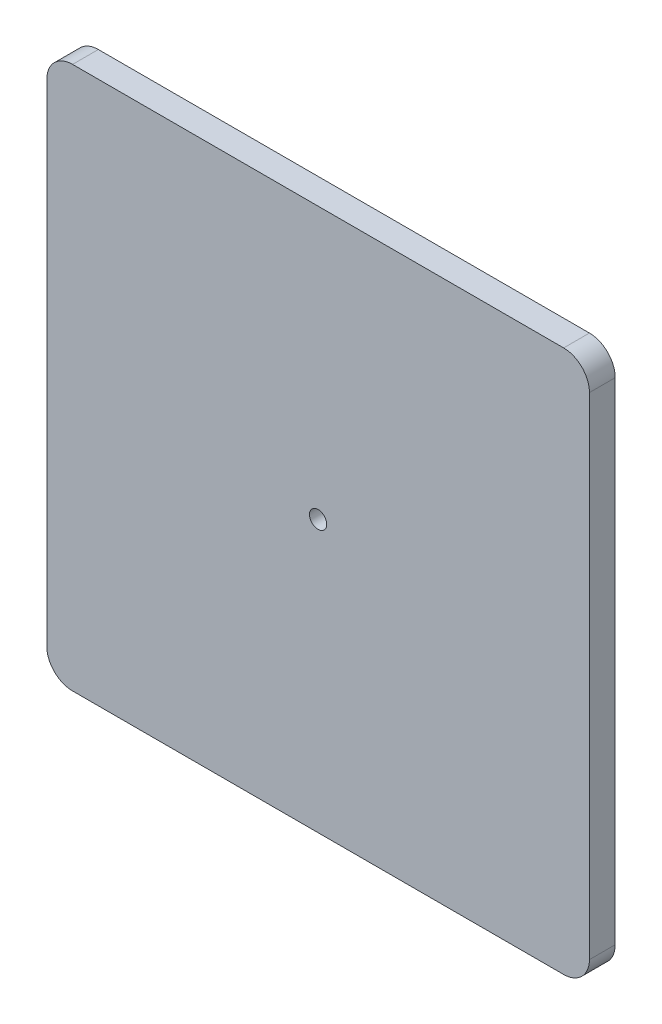
SolidWorks part; units mm, degrees
ref_plane "Front Plane" through (0, 0, 0) normal (0, 0, 1) x (1, 0, 0)
ref_plane "Top Plane" through (0, 0, 0) normal (0, 1, 0) x (1, 0, 0)
ref_plane "Right Plane" through (0, 0, 0) normal (1, 0, 0) x (0, 0, -1)
sketch "Baseplate" plane through (0, 0, 0) normal (0, 0, 1) x (1, 0, 0)
  line L2 (-100, 100) -> (100, 100)
  line L3 (-100, 100) -> (-100, -100)
  line L4 (-100, -100) -> (100, -100)
  line L5 (100, 100) -> (100, -100)
  line L6 (-100, 100) -> (100, -100) construction
  line L7 (-100, -100) -> (100, 100) construction
  point P2 (0, 0)
  dimension "D1" = 200
  dimension "D2" = 200
extrude "Boss-Extrude1" add sketch "Baseplate" along normal blind 9.5
sketch "LIDAR PLACEMENT" [suppressed] plane through (0, 0, 3) normal (0, 0, 1) x (1, 0, 0)
  circle A0 centre (0, 0) radius 51.65
  circle A1 centre (44.45, 0) radius 1.015
  dimension "D1" = 103.3
  dimension "2.03" = 2.03
  dimension "D2" = 44.45
fillet "Fillet1" radius 9.5 4 edges at (-100, -100, 4.75) (100, -100, 4.75) (100, 100, 4.75) (-100, 100, 4.75)
hole_wizard "1/4 Inch Bolt Hole" positions "Sketch7" profile "Sketch8" hole size "1/4" standard "ANSI Inch" end condition through all
sketch "Sketch7" plane through (0, 0, 0) normal (0, 0, -1) x (-1, 0, 0)
  point P0 (0, 0)
sketch "Sketch8" plane through (0, 0, 0) normal (1, 0, 0) x (0, 1, 0)
  line L0 (0, 0) -> (0, 9.5)
  line L1 (0, 9.5) -> (3.175, 9.5)
  line L2 (3.175, 9.5) -> (3.175, 0.635)
  line L3 (3.175, 0.635) -> (3.81, 0)
  line L5 (3.81, 0) -> (0, 0)
  line L6 (-3.175, 0.635) -> (-3.81, 0) construction
  line L11 (0, -6.35) -> (0, 107.95) construction
  dimension "Thru Hole Dia." = 6.35
  dimension "Thru Hole Depth" = 9.5
  dimension "Near C'Sink Dia." = 7.62
  dimension "Near C'Sink Angle" = 90
hole_wizard "5/32 Dowel Hole" positions "Sketch13" profile "Sketch14" hole size "5/32" standard "ANSI Inch"
sketch "Sketch13" plane through (0, 0, 0) normal (0, 0, -1) x (-1, 0, 0)
  point P0 (-44.5, 0)
  point P2 (44.45, 0)
  dimension "D1" = 44.45
  dimension "D2" = 44.5
sketch "Sketch14" plane through (44.5, 0, 0) normal (1, 0, 0) x (0, 1, 0)
  line L0 (0, 0) -> (0, 7.1923)
  line L1 (0, 7.1923) -> (1.9844, 6)
  line L2 (1.9844, 6) -> (1.9844, 0.5328)
  line L3 (1.9844, 0.5328) -> (2.6194, 0)
  line L5 (2.6194, 0) -> (0, 0)
  line L6 (-1.9844, 0.5328) -> (-2.6194, 0) construction
  line L10 (0, 7.1923) -> (-1.9844, 6) construction
  line L11 (0, -6.35) -> (0, 107.95) construction
  dimension "Hole Dia." = 3.9688
  dimension "Hole Depth" = 6
  dimension "Near C'Sink Dia." = 5.2387
  dimension "Near C'Sink Angle" = 100
  dimension "Drill Angle" = 118
